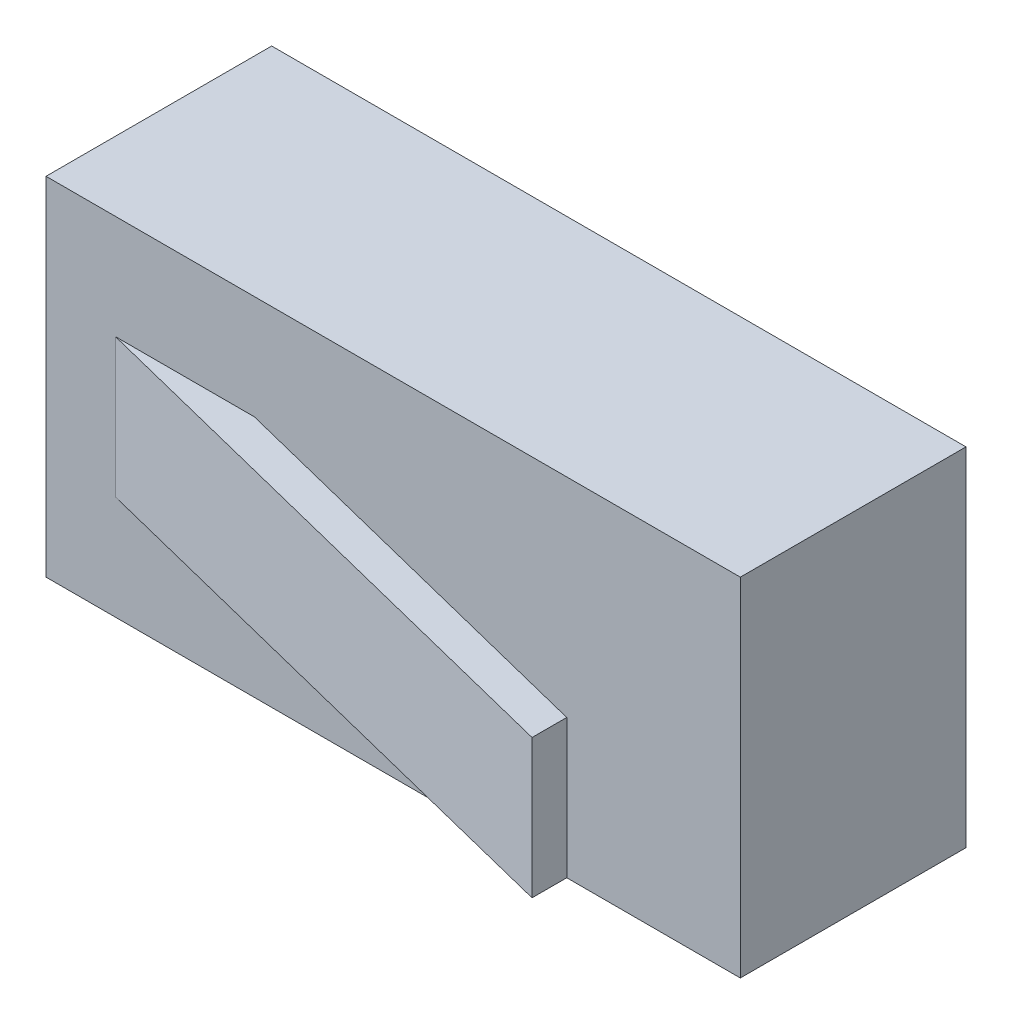
SolidWorks part; units mm, degrees
ref_plane "Plan de face" through (0, 0, 0) normal (0, 0, 1) x (1, 0, 0)
ref_plane "Plan de dessus" through (0, 0, 0) normal (0, 1, 0) x (1, 0, 0)
ref_plane "Plan de droite" through (0, 0, 0) normal (1, 0, 0) x (0, 0, -1)
sketch "Esquisse1" plane through (0, 0, 0) normal (0, 0, 1) x (1, 0, 0)
  line L1 (-10, 9) -> (10, 9)
  line L2 (-10, 9) -> (-10, 19)
  line L3 (-10, 19) -> (10, 19)
  line L4 (10, 9) -> (10, 19)
extrude "Boitier_microswitch" add sketch "Esquisse1" against normal blind 6.5 from offset 208.5
sketch "Esquisse2" plane through (0, 0, 0) normal (0, 1, 0) x (1, 0, 0)
  line L0 (-8, 208.5) -> (8, 204.5)
  line L1 (8, 204.5) -> (8, 205.5)
  line L2 (8, 205.5) -> (-8, 209.5)
  line L3 (-8, 209.5) -> (-8, 208.5)
extrude "Levier_detection" add sketch "Esquisse2" along normal blind 4 from offset 12
